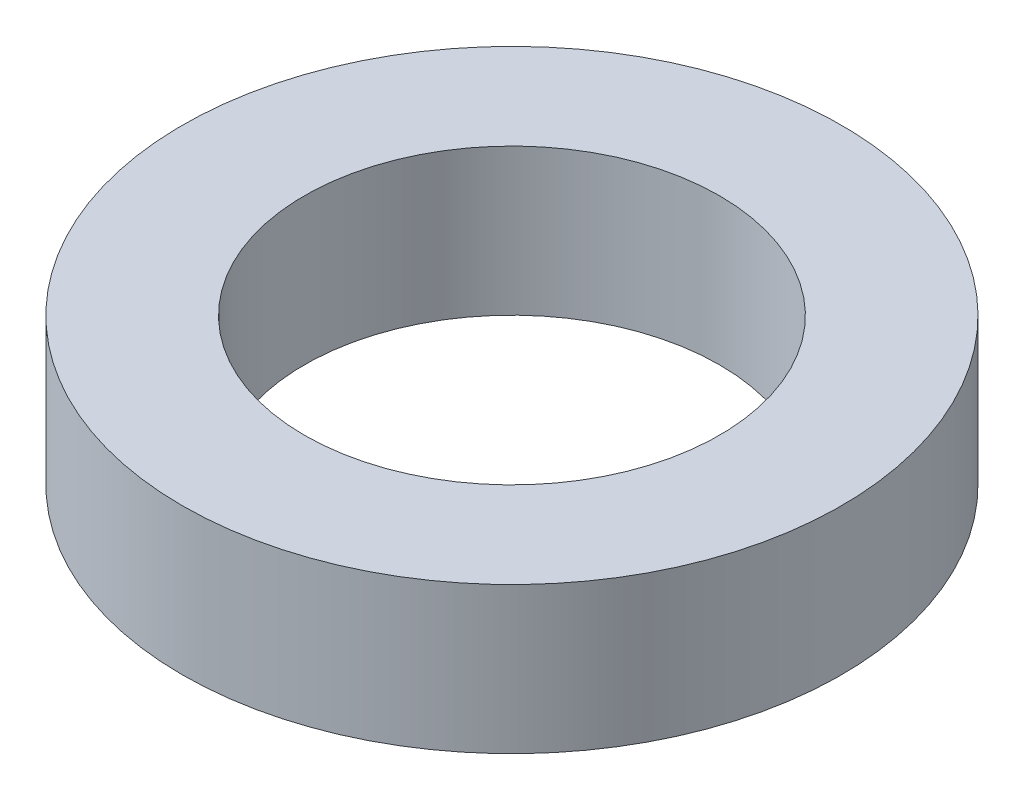
SolidWorks part; units mm, degrees
ref_plane "前视基准面" through (0, 0, 0) normal (0, 0, 1) x (1, 0, 0)
ref_plane "上视基准面" through (0, 0, 0) normal (0, 1, 0) x (1, 0, 0)
ref_plane "右视基准面" through (0, 0, 0) normal (1, 0, 0) x (0, 0, -1)
sketch "草图1" plane through (0, 0, 0) normal (0, 1, 0) x (1, 0, 0)
  circle A0 centre (0, 0) radius 17
  circle A1 centre (0, 0) radius 27
  dimension "D1" = 34
  dimension "D2" = 54
extrude "凸台-拉伸1" add sketch "草图1" along normal blind 12
